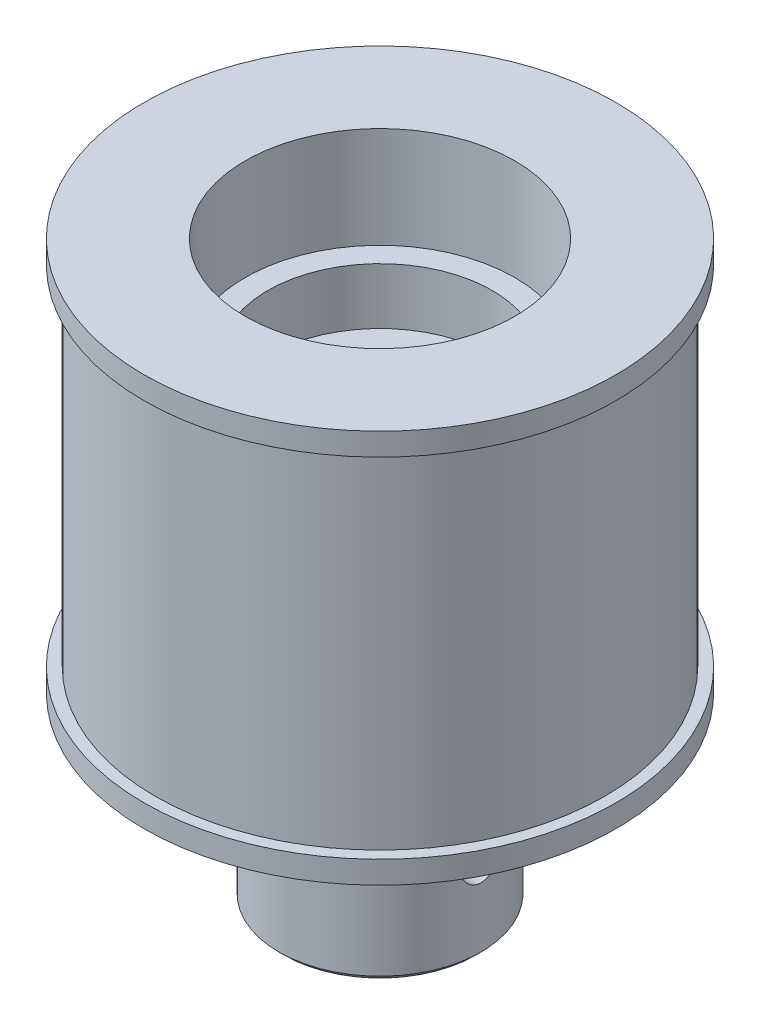
SolidWorks part; units mm, degrees
ref_plane "前视基准面" through (0, 0, 0) normal (0, 0, 1) x (1, 0, 0)
ref_plane "上视基准面" through (0, 0, 0) normal (0, 1, 0) x (1, 0, 0)
ref_plane "右视基准面" through (0, 0, 0) normal (1, 0, 0) x (0, 0, -1)
sketch "草图1" plane through (0, 0, 0) normal (0, 1, 0) x (1, 0, 0)
  circle A0 centre (0, 0) radius 21
  dimension "D1" = 42
extrude "凸台-拉伸1" add sketch "草图1" along normal mid plane 35
sketch "草图2" plane through (0, 0, 0) normal (0, 0, 1) x (1, 0, 0)
  line L0 (21, 15.5) -> (20, 15.5)
  line L1 (20, 15.5) -> (20, -15.5)
  line L2 (20, -15.5) -> (21, -15.5)
  line L3 (21, -15.5) -> (21, 15.5)
  line L4 (21, 17.5) -> (-21, 17.5) construction
  line L5 (-21, -17.5) -> (21, -17.5) construction
  dimension "D1" = 1
  dimension "D2" = 2
  dimension "D3" = 20
  dimension "D4" = 2
revolve "切除-旋转1" cut sketch "草图2" angle 360 about axis through (0, 17.5, 0) along (0, -1, 0)
sketch "草图3" plane through (0, 17.5, 0) normal (0, 1, 0) x (1, 0, 0)
  circle A0 centre (0, 0) radius 12
  dimension "D1" = 24
extrude "切除-拉伸1" cut sketch "草图3" against normal blind 9
sketch "草图4" plane through (0, -17.5, 0) normal (0, -1, 0) x (1, 0, 0)
  circle A0 centre (0, 0) radius 9
  dimension "D1" = 18
extrude "凸台-拉伸2" add sketch "草图4" along normal blind 16
ref_plane "基准面1" through (-43.6167, 0, 0) normal (1, 0, 0) x (0, 0, -1)
hole_wizard "M4 螺纹孔2" positions "草图11" profile "草图10" tap size "M4" standard "GB" end condition through all
sketch "草图11" plane through (-43.6167, 0, 0) normal (1, 0, 0) x (0, 0, -1)
  line L0 (0, -33.5) -> (0, -17.5) construction
  point P0 (0, -26)
  dimension "D1" = 26
sketch "草图10" plane through (-43.6167, -26, 0) normal (0, 1, 0) x (0, 0, 1)
  line L0 (0, 0) -> (0, 64.6167)
  line L1 (0, 64.6167) -> (1.65, 64.6167)
  line L2 (1.65, 64.6167) -> (1.65, 0)
  line L5 (1.65, 0) -> (0, 0)
  line L11 (0, -6.35) -> (0, 107.95) construction
  dimension "通孔螺纹孔钻头直径" = 3.3
  dimension "通孔螺纹孔钻头深度" = 64.6167
cosmetic thread "孔螺蚊线2" parameters "D2"=4
hole_wizard "Ø8.0 (8) 直径孔1" positions "草图13" profile "草图14" hole size "Ø8.0" standard "GB" end condition through all
sketch "草图13" plane through (0, -33.5, 0) normal (0, -1, 0) x (-1, 0, 0)
  point P0 (0, 0)
sketch "草图14" plane through (0, -33.5, 0) normal (1, 0, 0) x (0, 0, -1)
  line L0 (0, 0) -> (0, 51)
  line L1 (0, 51) -> (4, 51)
  line L2 (4, 51) -> (4, 0)
  line L5 (4, 0) -> (0, 0)
  line L11 (0, -6.35) -> (0, 107.95) construction
  dimension "通孔孔直径" = 8
  dimension "通孔孔深度" = 51
chamfer "倒角2" distance 0.5 angle 45 2 edges at (0, -33.5, -4) (0, -33.5, -9)
sketch "草图15" plane through (0, 8.5, 0) normal (0, 1, 0) x (1, 0, 0)
  circle A0 centre (0, 0) radius 10
  dimension "D1" = 20
extrude "切除-拉伸3" cut sketch "草图15" against normal blind 5
scale "Scale1" scale about centroid uniform scaling yes scale factor 2
